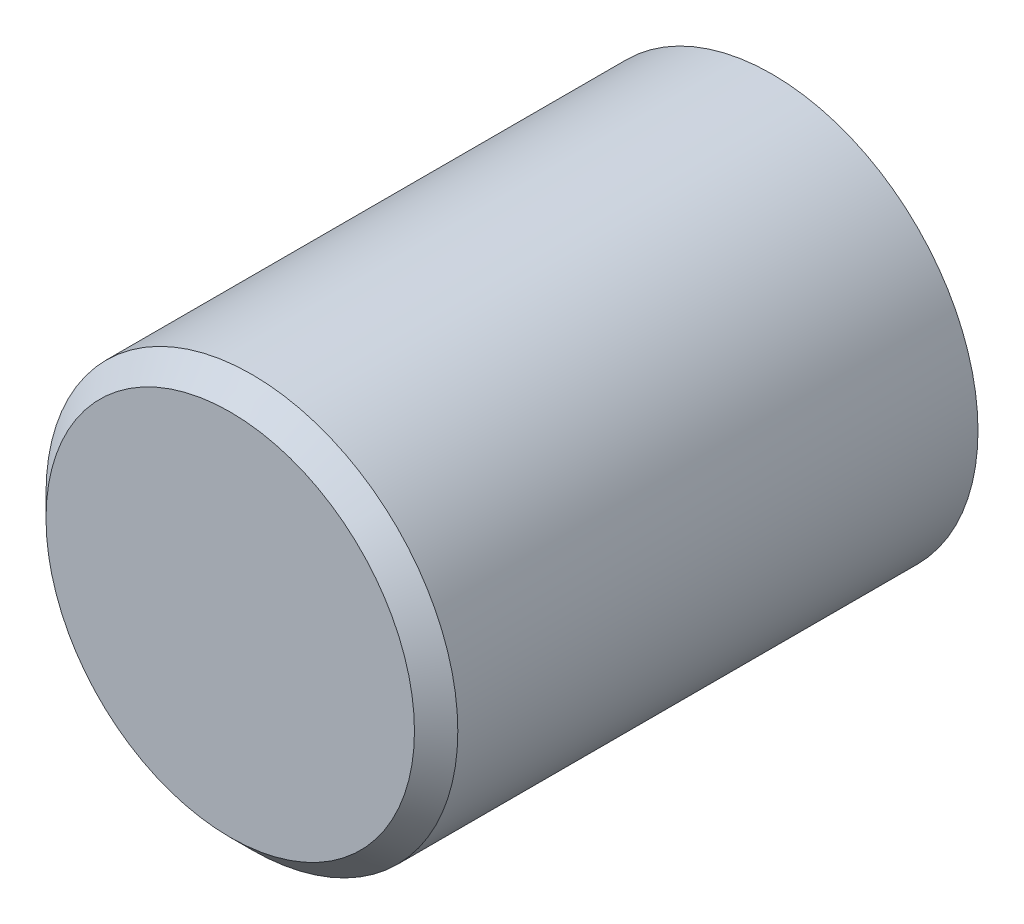
SolidWorks part; units mm, degrees
ref_plane "Alzado" through (0, 0, 0) normal (0, 0, 1) x (1, 0, 0)
ref_plane "Planta" through (0, 0, 0) normal (0, 1, 0) x (1, 0, 0)
ref_plane "Vista lateral" through (0, 0, 0) normal (1, 0, 0) x (0, 0, -1)
sketch "Croquis1" plane through (0, 0, 0) normal (0, 0, 1) x (1, 0, 0)
  circle A0 centre (0, 0) radius 19
  dimension "D1" = 38
extrude "Saliente-Extruir1" add sketch "Croquis1" against normal blind 50 contours A0
chamfer "Chaflán1" distance 2 angle 45 1 edges at (19, 0, 0)
sketch "Croquis2" plane through (0, 0, -50) normal (0, 0, -1) x (-1, 0, 0)
  circle A0 centre (0, 0) radius 8
  dimension "D1" = 16
extrude "Cortar-Extruir1" cut sketch "Croquis2" against normal blind 30
